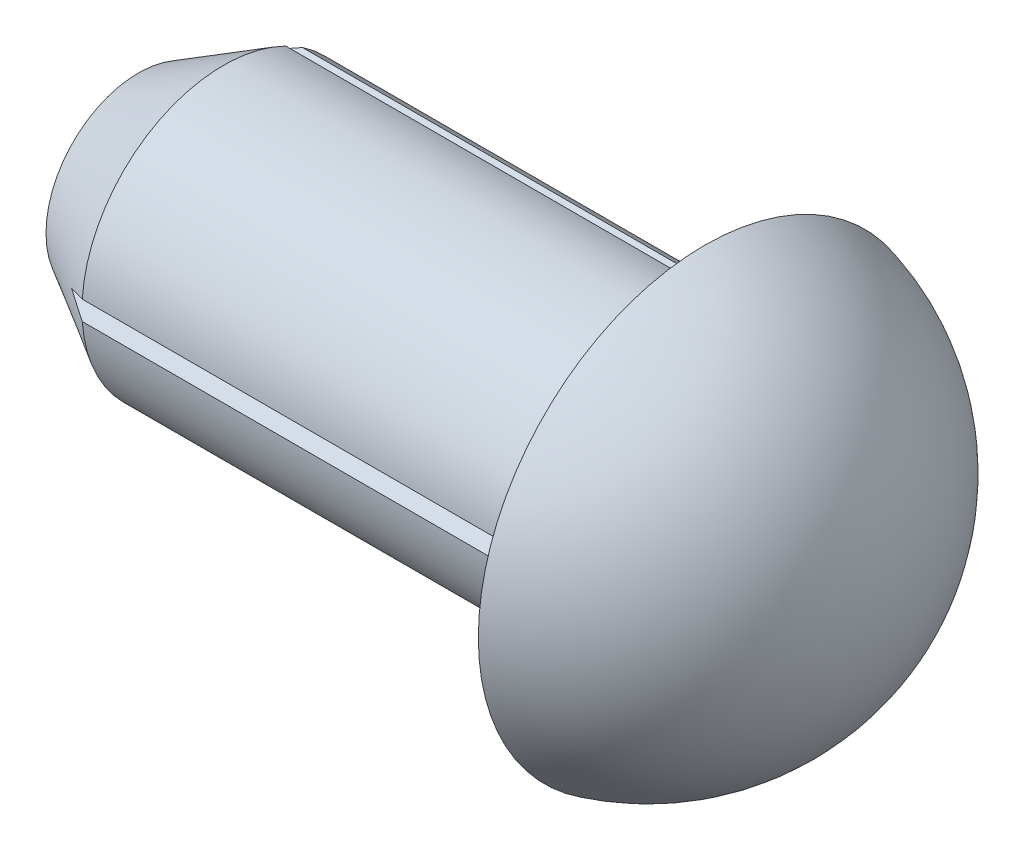
SolidWorks part; units mm, degrees
revolve "Base-Revolve" add sketch "Sketch1" angle 360 about L0
sketch "Sketch1" plane through (0, 0, 0) normal (0, 0, 1) x (1, 0, 0)
  line L0 (-40, 0) -> (40, 0) construction
  line L1 (-40, 0) -> (-40, 6.5359)
  line L2 (-34, 10) -> (0, 10)
  line L3 (0, 10) -> (0, 16)
  line L6 (12.4689, 0) -> (-40, 0)
  line L7 (-40, 6.5359) -> (-34, 10)
  arc A0 (12.4689, 0) -> (0, 16) centre (-4.0311, 0) ccw
  dimension "D1" = 30
  dimension "HeadRadius" = 16.5
  dimension "HeadDia" = 32
  dimension "Diameter" = 20
  dimension "Length" = 40
  dimension "ChamferLength" = 6
ref_plane "Plane1" through (0, 0, 0) normal (0, 0, 1) x (1, 0, 0)
ref_plane "Plane2" through (0, 0, 0) normal (0, 1, 0) x (1, 0, 0)
ref_plane "Plane3" through (0, 0, 0) normal (1, 0, 0) x (0, 0, -1)
sketch "Sketch2" plane through (-40, 0, 0) normal (-1, 0, 0) x (0, 0, 1)
  line L0 (0, 0) -> (12, 0) construction
  line L1 (9, 0) -> (10, 0.7002)
  line L2 (9, 0) -> (10, -0.7002)
  line L3 (10, -0.7002) -> (10, 0.7002)
  circle A0 centre (0, 0) radius 9 construction
  circle A1 centre (0, 0) radius 10 construction
  dimension "D1" = 18
  dimension "D2" = 70
  dimension "D3" = 35
extrude "Cut-Extrude1" cut sketch "Sketch2" against normal blind 37
pattern_circular "CirPattern1" count 3 over 360 about axis through (0, 0, 0) along (1, 0, 0) of "Cut-Extrude1"
equation "\"D1@Sketch2\" = \"Diameter@Sketch1\" * .9"
equation "\"D3@Sketch2\" = \"D2@Sketch2\" / 2"
equation "\"D1@Cut-Extrude1\" = \"Length@Sketch1\" - \"ChamferLength@Sketch1\" / 2"
